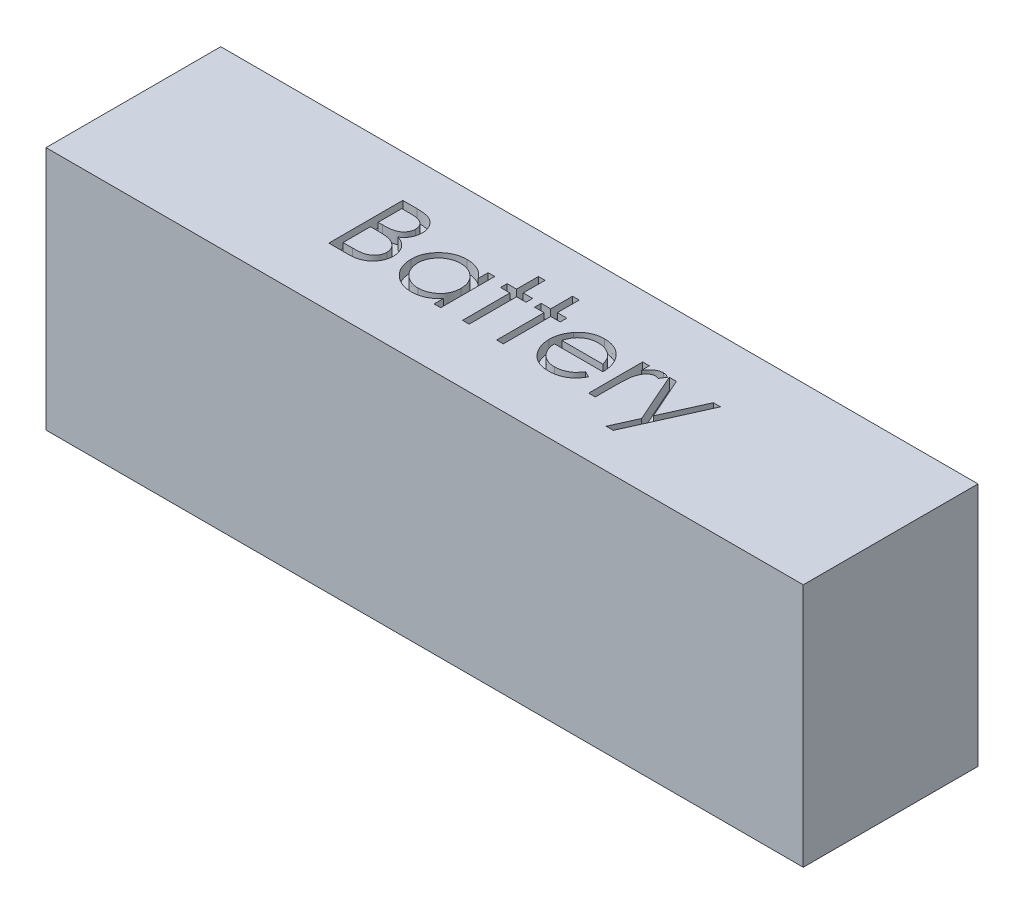
SolidWorks part; units mm, degrees
ref_plane "Front Plane" through (0, 0, 0) normal (0, 0, 1) x (1, 0, 0)
ref_plane "Top Plane" through (0, 0, 0) normal (0, 1, 0) x (1, 0, 0)
ref_plane "Right Plane" through (0, 0, 0) normal (1, 0, 0) x (0, 0, -1)
sketch "Szkic1" plane through (0, 0, 0) normal (0, 1, 0) x (1, 0, 0)
  line L0 (-65, -15) -> (65, 15) construction
  line L1 (-65, 15) -> (65, 15)
  line L2 (-65, 15) -> (-65, -15)
  line L3 (-65, -15) -> (65, -15)
  line L4 (65, 15) -> (65, -15)
  dimension "D1" = 130
  dimension "D2" = 30
extrude "Dodanie-wyciągnięcie1" add sketch "Szkic1" along normal blind 42
sketch "Szkic2" plane through (0, 42, 0) normal (0, 1, 0) x (1, 0, 0)
  text T0 "Battery" font "Century Gothic" height in points 48
extrude "Wytnij-wyciągnięcie1" cut sketch "Szkic2" against normal blind 2
